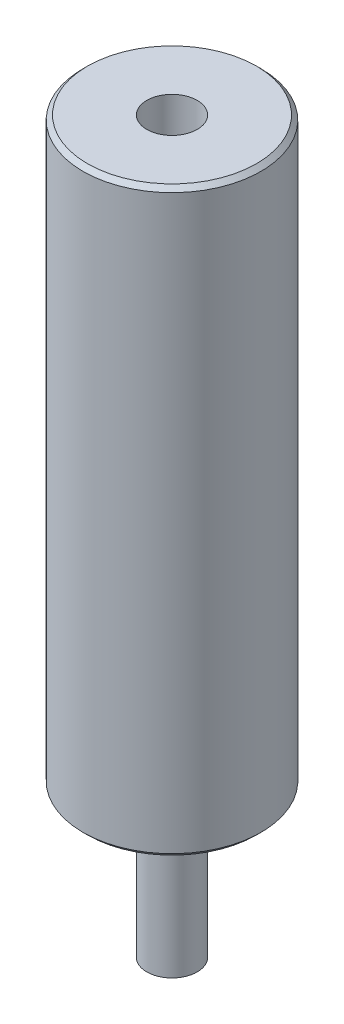
SolidWorks part; units mm, degrees
ref_plane "Plano frontal" through (0, 0, 0) normal (0, 0, 1) x (1, 0, 0)
ref_plane "Plano superior" through (0, 0, 0) normal (0, 1, 0) x (1, 0, 0)
ref_plane "Plano direito" through (0, 0, 0) normal (1, 0, 0) x (0, 0, -1)
ref_plane "Plano1" through (0, 0, 0) normal (0, 0, -1) x (-1, 0, 0)
sketch "Esboço1" plane through (0, 0, 0) normal (0, 0, -1) x (-1, 0, 0)
  line L0 (-1.7, 0) -> (0, 0)
  line L1 (0, 0) -> (0, 39.2)
  line L2 (0, 39.2) -> (-1.7, 39.2)
  line L3 (-1.7, 39.2) -> (-1.7, 49.2)
  line L4 (-1.7, 49.2) -> (-5.7, 49.2)
  line L5 (-5.7, 49.2) -> (-6, 48.9)
  line L6 (-6, 48.9) -> (-6, 10.3)
  line L7 (-6, 10.3) -> (-5.7, 10)
  line L8 (-5.7, 10) -> (-2.2, 10)
  line L9 (-1.7, 9.5) -> (-1.7, 0)
  line L10 (0, 0) -> (0, 49.2) construction
  arc A0 (-2.2, 10) -> (-1.7, 9.5) centre (-2.2, 9.5) cw
revolve "Revolução1" add sketch "Esboço1" angle 360 about L10
